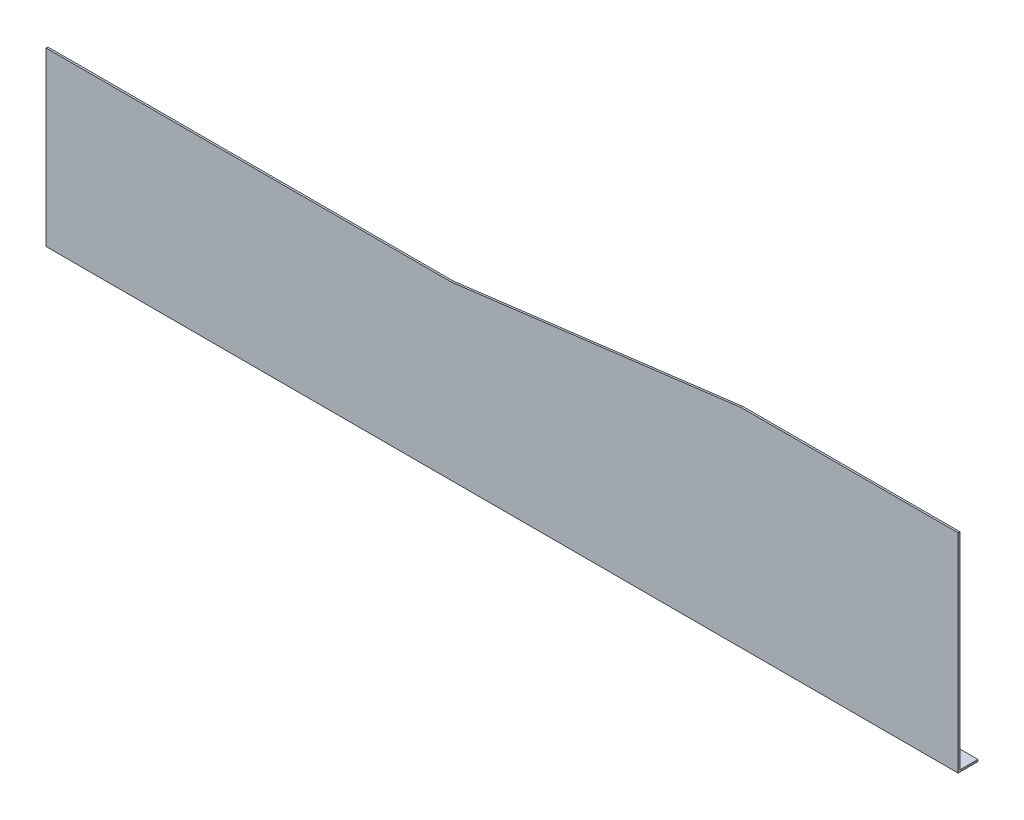
SolidWorks part; units mm, degrees
ref_plane "Front Plane" through (0, 0, 0) normal (0, 0, 1) x (1, 0, 0)
ref_plane "Top Plane" through (0, 0, 0) normal (0, 1, 0) x (1, 0, 0)
ref_plane "Right Plane" through (0, 0, 0) normal (1, 0, 0) x (0, 0, -1)
sketch "Sketch1" plane through (0, 0, 0) normal (0, 0, 1) x (1, 0, 0)
  line L0 (0, 0) -> (0, 118.73)
  line L1 (0, 118.73) -> (280, 118.73)
  line L2 (280, 118.73) -> (480, 143.73)
  line L3 (480, 143.73) -> (630, 143.73)
  line L4 (630, 143.73) -> (630, 0)
  line L5 (630, 0) -> (0, 0)
  dimension "D1" = 143.73
  dimension "D2" = 118.73
  dimension "D3" = 630
  dimension "D4" = 280
  dimension "D5" = 200
extrude "Boss-Extrude1" add sketch "Sketch1" along normal blind 1.27
sketch "Sketch2" plane through (0, 0, 1.27) normal (0, 0, 1) x (1, 0, 0)
  line L0 (630, 0) -> (630, 143.73) construction
  line L1 (0, 0) -> (630, 0)
  line L2 (0, 0) -> (0, 1.27)
  line L3 (0, 1.27) -> (630, 1.27)
  line L4 (630, 0) -> (630, 1.27)
  dimension "D1" = 1.27
extrude "Boss-Extrude2" add sketch "Sketch2" against normal blind 13.77
